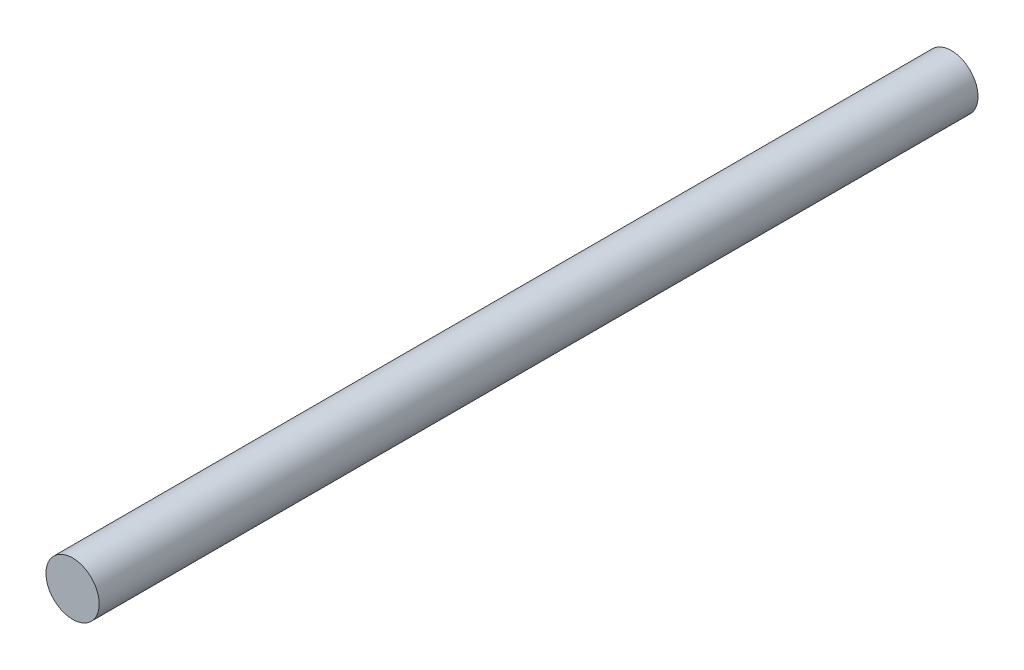
SolidWorks part; units mm, degrees
ref_plane "前视基准面" through (0, 0, 0) normal (0, 0, 1) x (1, 0, 0)
ref_plane "上视基准面" through (0, 0, 0) normal (0, 1, 0) x (1, 0, 0)
ref_plane "右视基准面" through (0, 0, 0) normal (1, 0, 0) x (0, 0, -1)
other "Configuration Table"
sketch "草图1" plane through (0, 0, 0) normal (0, 0, 1) x (1, 0, 0)
  circle A0 centre (0, 0) radius 10
extrude "凸台-拉伸1" add sketch "草图1" along normal blind 330
